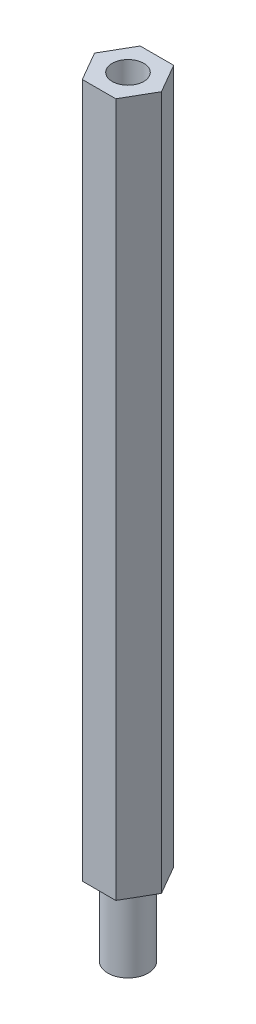
SolidWorks part; units mm, degrees
ref_plane "前视基准面" through (0, 0, 0) normal (0, 0, 1) x (1, 0, 0)
ref_plane "上视基准面" through (0, 0, 0) normal (0, 1, 0) x (1, 0, 0)
ref_plane "右视基准面" through (0, 0, 0) normal (1, 0, 0) x (0, 0, -1)
sketch "草图4" plane through (0, 0, 0) normal (0, 1, 0) x (1, 0, 0)
  line L0 (-12.7945, 0) -> (16.3015, 0) construction
  line L2 (1.325, -2.295) -> (2.65, 0)
  line L3 (2.65, 0) -> (1.325, 2.295)
  line L4 (1.325, 2.295) -> (-1.325, 2.295)
  line L5 (-1.325, 2.295) -> (-2.65, 0)
  line L6 (-2.65, 0) -> (-1.325, -2.295)
  line L7 (-1.325, -2.295) -> (1.325, -2.295)
  circle A0 centre (0, 0) radius 2.295 construction
  dimension "D1" = 5.3
extrude "凸台-拉伸1" add sketch "草图4" along normal blind 55
sketch "草图6" plane through (0, 0, 0) normal (0, -1, 0) x (-1, 0, 0)
  circle A0 centre (0, 0) radius 1.6
  dimension "D1" = 3.2
extrude "凸台-拉伸2" add sketch "草图6" along normal blind 6
cosmetic thread "装饰螺纹线1" parameters "D2"=2.5
sketch "草图7" plane through (0, 55, 0) normal (0, 1, 0) x (1, 0, 0)
  circle A0 centre (0, 0) radius 1.25
  dimension "D1" = 2.5
extrude "切除-拉伸1" cut sketch "草图7" against normal blind 5
cosmetic thread "装饰螺纹线2" parameters "D2"=3
